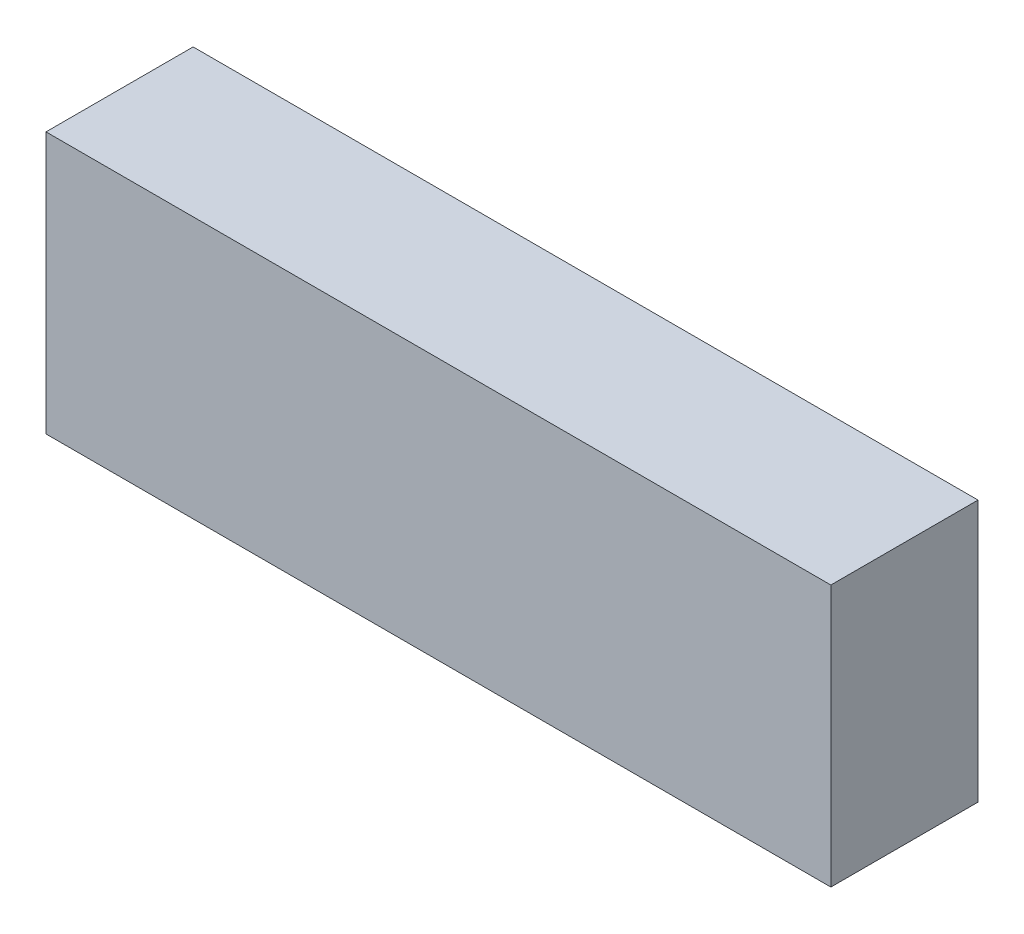
SolidWorks part; units mm, degrees
ref_plane "Ebene vorne" through (0, 0, 0) normal (0, 0, 1) x (1, 0, 0)
ref_plane "Ebene oben" through (0, 0, 0) normal (0, 1, 0) x (1, 0, 0)
ref_plane "Ebene rechts" through (0, 0, 0) normal (1, 0, 0) x (0, 0, -1)
sketch "Skizze1" plane through (0, 0, 0) normal (0, 0, 1) x (1, 0, 0)
  line L0 (-2.54, 0.889) -> (2.794, 0.889)
  line L1 (2.794, 0.889) -> (2.794, -0.889)
  line L2 (2.794, -0.889) -> (-2.54, -0.889)
  line L3 (-2.54, -0.889) -> (-2.54, 0.889)
extrude "Component_Outline" add sketch "Skizze1" along normal blind 1 separate body
sketch3d "3D-Skizze1"
  line L0 (0, 0, 0) -> (1, 0, 0)
  line L1 (0, 0, 0) -> (0, 1, 0)
  line L2 (0, 0, 0) -> (0, 0, 1)
  point P0 (0, 0, 0)
